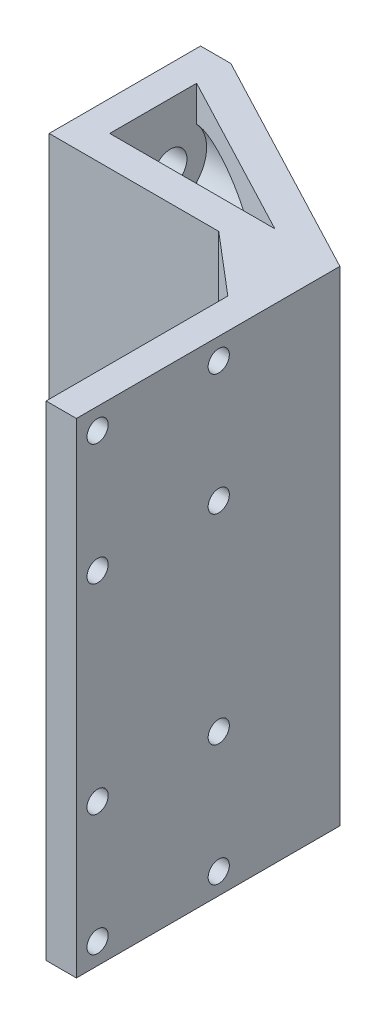
SolidWorks part; units mm, degrees
ref_plane "Plan de face" through (0, 0, 0) normal (0, 0, 1) x (1, 0, 0)
ref_plane "Plan de dessus" through (0, 0, 0) normal (0, 1, 0) x (1, 0, 0)
ref_plane "Plan de droite" through (0, 0, 0) normal (1, 0, 0) x (0, 0, -1)
sketch "Esquisse1" plane through (0, 0, 0) normal (0, 0, 1) x (1, 0, 0)
  line L1 (-33.3969, 24.3516) -> (9.6031, 24.3516)
  line L2 (-33.3969, 24.3516) -> (-33.3969, -55.6484)
  line L3 (-33.3969, -55.6484) -> (9.6031, -55.6484)
  line L4 (9.6031, 24.3516) -> (9.6031, -55.6484)
  dimension "D1" = 80
  dimension "D2" = 43
extrude "Boss.-Extru.1" add sketch "Esquisse1" along normal blind 5
sketch "Esquisse2" plane through (0, 0, 5) normal (0, 0, -1) x (-1, 0, 0)
  line L0 (-9.6031, 24.3516) -> (33.3969, 24.3516) construction
  line L1 (-9.6031, -55.6484) -> (-4.6031, -55.6484)
  line L2 (-9.6031, -55.6484) -> (-9.6031, 24.3516)
  line L3 (-9.6031, 24.3516) -> (-4.6031, 24.3516)
  line L4 (-4.6031, -55.6484) -> (-4.6031, 24.3516)
  dimension "D1" = 5
extrude "Boss.-Extru.2" add sketch "Esquisse2" against normal blind 38.5
sketch "Esquisse3" plane through (9.6031, 0, 0) normal (1, 0, 0) x (0, 0, -1)
  line L0 (-20, -52.1484) -> (-40, -52.1484) construction
  line L1 (-40, -52.1484) -> (-40, -32.1484) construction
  line L2 (-40, 20.8516) -> (-20, 20.8516) construction
  line L3 (-20, 20.8516) -> (-20, 0.8516) construction
  line L4 (-43.5, 24.3516) -> (-43.5, -55.6484) construction
  line L5 (-43.5, -55.6484) -> (0, -55.6484) construction
  line L6 (-43.5, 24.3516) -> (0, 24.3516) construction
  circle A0 centre (-40, -52.1484) radius 1.75
  circle A1 centre (-40, -32.1484) radius 1.75
  circle A2 centre (-20, -32.1484) radius 1.75
  circle A3 centre (-20, -52.1484) radius 1.75
  circle A4 centre (-40, 0.8516) radius 1.75
  circle A5 centre (-40, 20.8516) radius 1.75
  circle A6 centre (-20, 20.8516) radius 1.75
  circle A7 centre (-20, 0.8516) radius 1.75
  dimension "D1" = 3.5
  dimension "D2" = 20
  dimension "D3" = 3.5
  dimension "D4" = 3.5
  dimension "D5" = 3.5
extrude "Enlèv. mat.-Extru.1" cut sketch "Esquisse3" against normal up to next
sketch "Esquisse4" plane through (0, 0, 0) normal (0, 0, -1) x (-1, 0, 0)
  line L0 (-9.6031, 24.3516) -> (33.3969, 24.3516) construction
  line L1 (33.3969, -55.6484) -> (28.3969, -55.6484)
  line L2 (33.3969, -55.6484) -> (33.3969, 24.3516)
  line L3 (33.3969, 24.3516) -> (28.3969, 24.3516)
  line L4 (28.3969, -55.6484) -> (28.3969, 24.3516)
  dimension "D1" = 5
extrude "Boss.-Extru.3" add sketch "Esquisse4" along normal blind 20
sketch "Esquisse5" plane through (-28.3969, 0, 0) normal (1, 0, 0) x (0, 0, -1)
  line L0 (20, -55.6484) -> (0, -55.6484) construction
  line L1 (20, 24.3516) -> (0, 24.3516) construction
  circle A0 centre (10, 14.3516) radius 2.75
  circle A1 centre (10, -5.6484) radius 2.75
  circle A2 centre (10, -25.6484) radius 2.75
  circle A3 centre (10, -45.6484) radius 2.75
  point P12 (10, 24.3516)
  dimension "D1" = 5.5
  dimension "D2" = 10
  dimension "D3" = 10
  dimension "D4" = 20
  dimension "D5" = 20
extrude "Enlèv. mat.-Extru.2" cut sketch "Esquisse5" against normal up to next
sketch "Esquisse6" plane through (0, 0, 0) normal (0, 0, -1) x (-1, 0, 0)
  line L0 (28.3969, -55.6484) -> (-9.6031, -55.6484) construction
  line L1 (28.3969, 24.3516) -> (28.3969, -55.6484) construction
  circle A0 centre (18.3969, -45.6484) radius 1.5
  dimension "D2" = 3
  dimension "D1" = 10
  dimension "D3" = 10
extrude "Enlèv. mat.-Extru.3" cut sketch "Esquisse6" against normal up to next
sketch "Esquisse7" plane through (0, 24.3516, 0) normal (0, 1, 0) x (1, 0, 0)
  line L0 (9.6031, 0) -> (-28.3969, 20)
  line L1 (-28.3969, 20) -> (-28.3969, 14.3498)
  line L2 (-28.3969, 20) -> (-28.3969, 0) construction
  line L3 (-28.3969, 14.3498) -> (-1.1323, 0)
  line L4 (9.6031, 0) -> (-28.3969, 0) construction
  line L5 (-1.1323, 0) -> (9.6031, 0)
  dimension "D1" = 5
extrude "Boss.-Extru.4" add sketch "Esquisse7" against normal up to surface (80 mm away) up to face at (-11.8969, -55.6484, 7.125)
sketch "Esquisse8" plane through (-28.3969, 0, 0) normal (1, 0, 0) x (0, 0, -1)
  circle A0 centre (10, -45.6484) radius 6
  circle A1 centre (10, -25.6484) radius 6
  circle A2 centre (10, -5.6484) radius 6
  circle A3 centre (10, 14.3516) radius 6
  dimension "D1" = 12
extrude "Enlèv. mat.-Extru.4" cut sketch "Esquisse8" along normal up to next
chamfer "Chanfrein2" distance 8.5 distance2 10 1 edges at (4.6031, -15.6484, 5)
